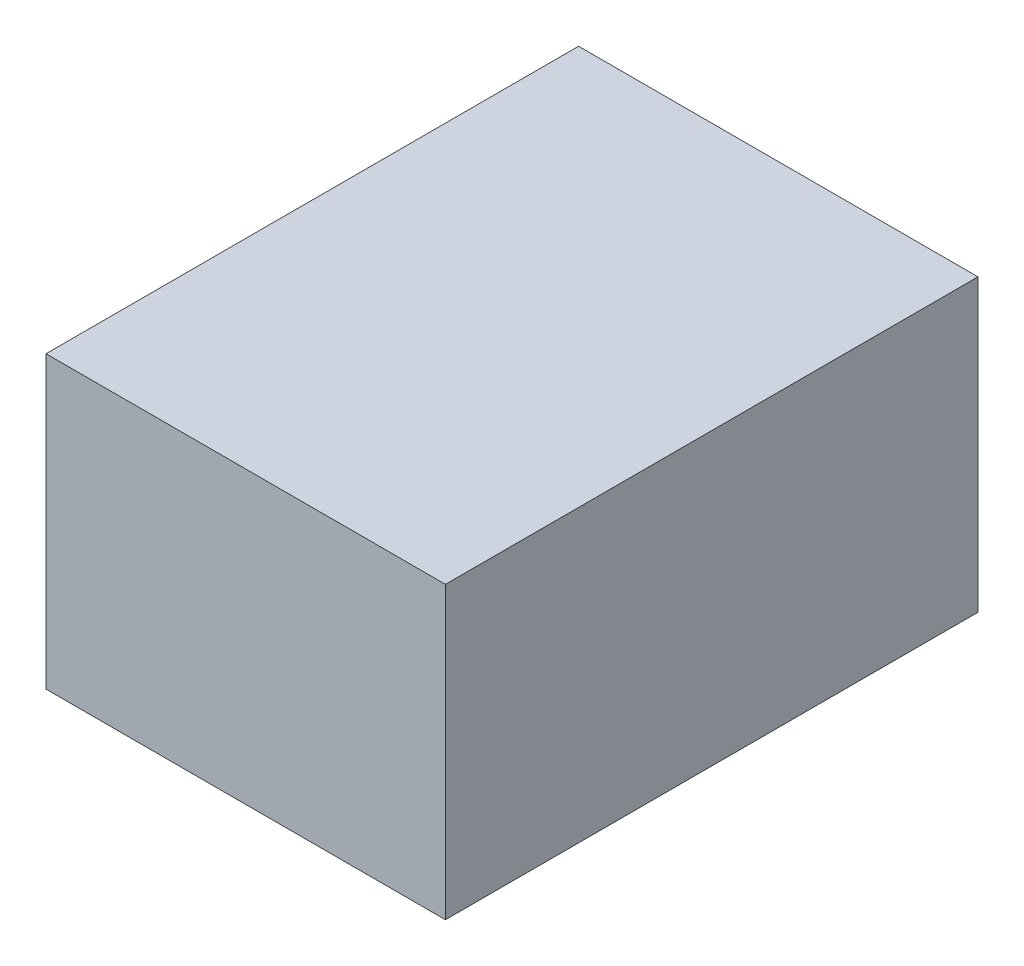
SolidWorks part; units mm, degrees
ref_plane "Front Plane" through (0, 0, 0) normal (0, 0, 1) x (1, 0, 0)
ref_plane "Top Plane" through (0, 0, 0) normal (0, 1, 0) x (1, 0, 0)
ref_plane "Right Plane" through (0, 0, 0) normal (1, 0, 0) x (0, 0, -1)
sketch "Sketch2" plane through (0, 0, 0) normal (0, 0, 1) x (1, 0, 0)
  line L0 (0, 0) -> (838.2, 0)
  line L1 (0, 0) -> (0, 609.6)
  line L2 (838.2, 0) -> (838.2, 609.6)
  line L3 (838.2, 609.6) -> (0, 609.6)
  dimension "D1" = 838.2
  dimension "D2" = 609.6
extrude "Boss-Extrude1" add sketch "Sketch2" along normal blind 1117.6 contours L3 L1 L0 L2
shell "Shell1" thickness 6.35
